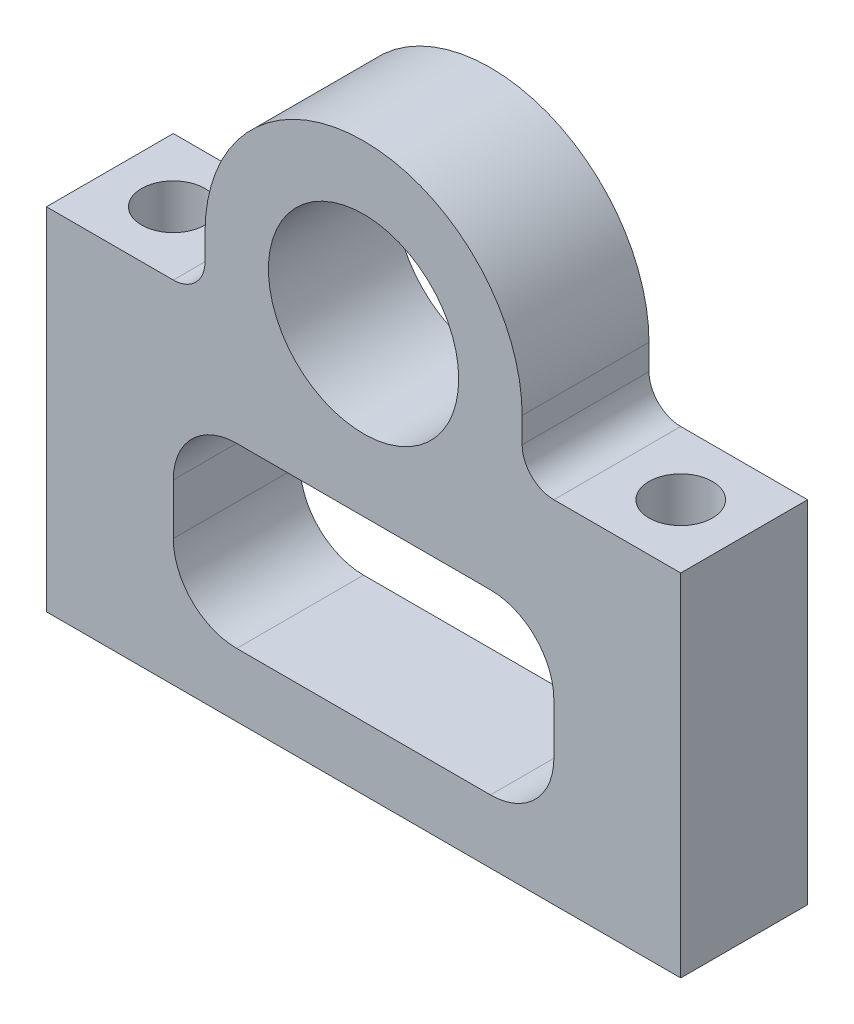
SolidWorks part; units mm, degrees
ref_plane "Front Plane" through (0, 0, 0) normal (0, 0, 1) x (1, 0, 0)
ref_plane "Top Plane" through (0, 0, 0) normal (0, 1, 0) x (1, 0, 0)
ref_plane "Right Plane" through (0, 0, 0) normal (1, 0, 0) x (0, 0, -1)
sketch "Sketch1" plane through (0, 0, 0) normal (0, 0, 1) x (1, 0, 0)
  line L0 (0, 0) -> (0, 14.5) construction
  line L1 (0, 0) -> (-25, 0)
  line L2 (0, 0) -> (25, 0)
  line L3 (-25, 10) -> (-25, 0)
  line L4 (0, 14.5) -> (0, 30) construction
  line L5 (-12.5, 12.5) -> (-12.5, 14.5)
  line L6 (12.5, 12.5) -> (12.5, 14.5)
  line L7 (-15, 10) -> (-25, 10)
  line L9 (25, 10) -> (25, 0)
  line L10 (15, 10) -> (25, 10)
  circle A0 centre (0, 14.5) radius 7.5
  arc A1 (15, 10) -> (12.5, 12.5) centre (15, 12.5) cw
  arc A2 (-15, 10) -> (-12.5, 12.5) centre (-15, 12.5) ccw
  arc A6 (12.5, 14.5) -> (-12.5, 14.5) centre (0, 14.5) ccw
  point P15 (12.5, 10)
  point P18 (-12.5, 10)
  point P21 (12.5, 30)
  point P24 (-12.5, 30)
  dimension "D1" = 2.5
extrude "Boss-Extrude1" add sketch "Sketch1" along normal blind 10
sketch "Sketch4" plane through (0, 10, 0) normal (0, 1, 0) x (1, 0, 0)
  line L0 (-25, -5) -> (-20, -5) construction
  line L1 (-25, -10) -> (-25, 0) construction
  line L2 (0, 0) -> (0, 6.4294) construction
  circle A0 centre (-20, -5) radius 2.5
  circle A1 centre (20, -5) radius 2.5
extrude "Cut-Extrude1" cut sketch "Sketch4" against normal blind 20
sketch "Sketch5" plane through (0, 0, 0) normal (0, -1, 0) x (1, 0, 0)
  line L1 (-25, 10) -> (25, 10)
  line L2 (-25, 10) -> (-25, 0)
  line L3 (-25, 0) -> (25, 0)
  line L4 (25, 10) -> (25, 0)
  circle A0 centre (-20, 5) radius 2.5
  circle A1 centre (20, 5) radius 2.5
extrude "Boss-Extrude2" add sketch "Sketch5" along normal blind 17.65
sketch "Sketch6" plane through (0, 0, 10) normal (0, 0, 1) x (1, 0, 0)
  line L0 (0, -17.65) -> (0, -5.65) construction
  line L1 (25, -17.65) -> (-25, -17.65) construction
  line L3 (10, 1.35) -> (-10, 1.35)
  line L4 (15, -3.65) -> (15, -7.65)
  line L5 (10, -12.65) -> (-10, -12.65)
  line L6 (-15, -3.65) -> (-15, -7.65)
  line L7 (15, 1.35) -> (-15, -12.65) construction
  line L8 (15, -12.65) -> (-15, 1.35) construction
  arc A0 (10, 1.35) -> (15, -3.65) centre (10, -3.65) cw
  arc A1 (15, -7.65) -> (10, -12.65) centre (10, -7.65) cw
  arc A2 (-10, -12.65) -> (-15, -7.65) centre (-10, -7.65) cw
  arc A3 (-15, -3.65) -> (-10, 1.35) centre (-10, -3.65) cw
  dimension "D3" = 5
  dimension "D1" = 5
  dimension "D2" = 30
extrude "Cut-Extrude3" cut sketch "Sketch6" against normal blind 17.65
